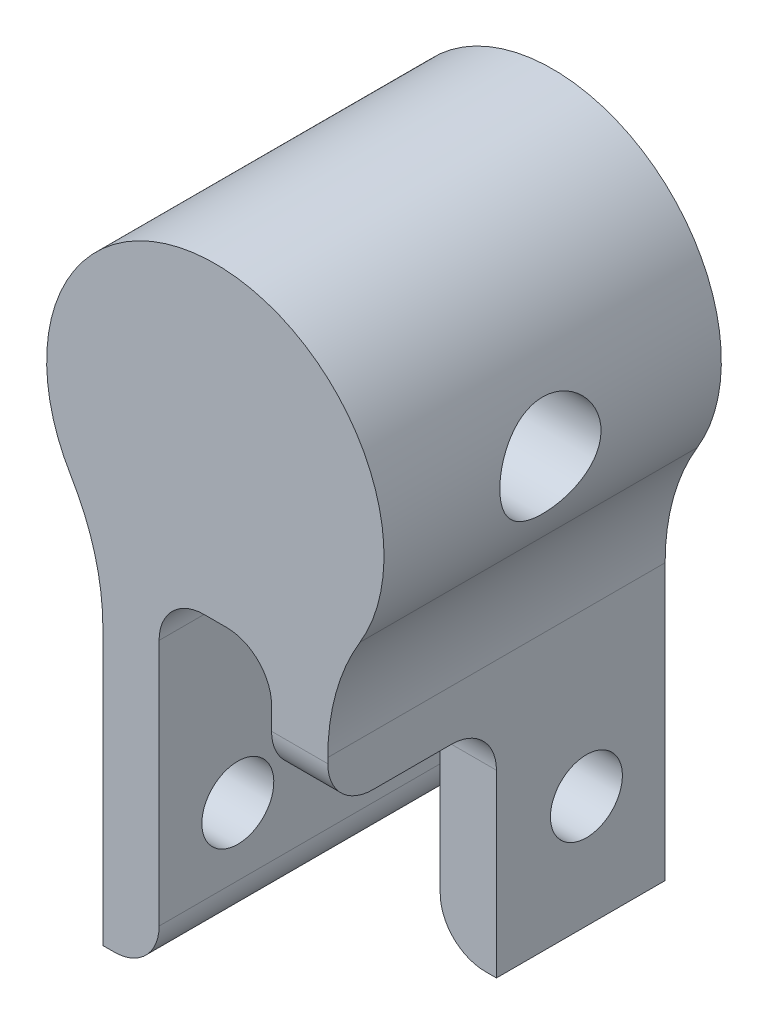
SolidWorks part; units mm, degrees
material "PUR"
ref_plane "Front Plane" through (0, 0, 0) normal (0, 0, 1) x (1, 0, 0)
ref_plane "Top Plane" through (0, 0, 0) normal (0, 1, 0) x (1, 0, 0)
ref_plane "Right Plane" through (0, 0, 0) normal (1, 0, 0) x (0, 0, -1)
sketch "Sketch2" plane through (0, 0, 0) normal (0, 0, 1) x (1, 0, 0)
  line L8 (0, 0) -> (0, -6.2546) construction
  line L9 (0, -6.2546) -> (0, -21.2546) construction
  line L10 (-2.5, -6.2546) -> (-2.5, -21.2546)
  line L11 (2.5, -6.2546) -> (2.5, -21.2546)
  line L12 (-5, -6.2546) -> (-5, -21.2546)
  line L13 (5, -6.2546) -> (5, -21.2546)
  line L14 (-5, -6.2546) -> (-5, -5.5902)
  line L15 (5, -6.2546) -> (5, -5.5902)
  line L16 (-2.5, -6.2546) -> (2.5, -6.2546)
  line L17 (-5, -21.2546) -> (-2.5, -21.2546)
  line L18 (2.5, -21.2546) -> (5, -21.2546)
  arc A0 (5, -5.5902) -> (-5, -5.5902) centre (0, 0) ccw
  dimension "D1" = 2.5
  dimension "D3" = 15
  dimension "D2" = 2.5
  dimension "D4" = 5
  dimension "D5" = 5
  dimension "D6" = 15
extrude "Boss-Extrude1" add sketch "Sketch2" along normal blind 15
sketch "Sketch3" plane through (0, 0, 0) normal (0, 0, -1) x (-1, 0, 0)
  circle A0 centre (0, 0) radius 2.05
  arc A1 (5, -5.5902) -> (-5, -5.5902) centre (0, 0) ccw construction
  dimension "D1" = 4.1
fillet "Fillet1" radius 10 2 edges at (5, -5.5902, 7.5) (-5, -5.5902, 7.5)
sketch "Sketch7" plane through (5, 0, 0) normal (1, 0, 0) x (0, 0, -1)
  line L1 (-15, -21.2546) -> (-7.5, -21.2546)
  line L2 (-15, -21.2546) -> (-15, -11.2546)
  line L3 (-15, -11.2546) -> (-7.5, -11.2546)
  line L4 (-7.5, -21.2546) -> (-7.5, -11.2546)
  dimension "D1" = 10
  dimension "D2" = 7.5
extrude "Cut-Extrude4" cut sketch "Sketch7" against normal up to next
sketch "Sketch9" plane through (-5, 0, 0) normal (-1, 0, 0) x (0, 0, 1)
  line L0 (0, -9.0139) -> (0, -21.2546) construction
  line L1 (15, -21.2546) -> (0, -21.2546) construction
  circle A0 centre (3.5, -16.2546) radius 1.6
  dimension "D1" = 3.2
  dimension "D2" = 3.5
  dimension "D3" = 5
sketch "Sketch10" plane through (-5, 0, 0) normal (-1, 0, 0) x (0, 0, 1)
  line L0 (15, -21.2546) -> (0, -21.2546) construction
  line L1 (15, -9.0139) -> (15, -21.2546) construction
  circle A0 centre (11.5, -16.2546) radius 1.6
  dimension "D1" = 3.2
  dimension "D2" = 5
  dimension "D3" = 3.5
extrude "Cut-Extrude7" cut sketch "Sketch10" against normal up to next
extrude "Cut-Extrude8" cut sketch "Sketch9" against normal through all
fillet "Fillet3" radius 2 6 edges at (3.75, -11.2546, 7.5) (3.75, -11.2546, 15) (2.5, -21.2546, 3.75) (-2.5, -21.2546, 7.5) (2.5, -6.2546, 7.5) (-2.5, -6.2546, 7.5)
extrude "Cut-Extrude9" cut sketch "Sketch3" against normal blind 10
sketch "Sketch11" plane through (-5, 0, 0) normal (-1, 0, 0) x (0, 0, 1)
  line L0 (0, 7.5) -> (0, -3.8631) construction
  line L1 (15, 7.5) -> (0, 7.5) construction
  circle A0 centre (7.6, 0) radius 2.25
  dimension "D1" = 4.5
  dimension "D2" = 7.6
  dimension "D3" = 7.5
extrude "Cut-Extrude10" cut sketch "Sketch11" against normal mid plane 30
